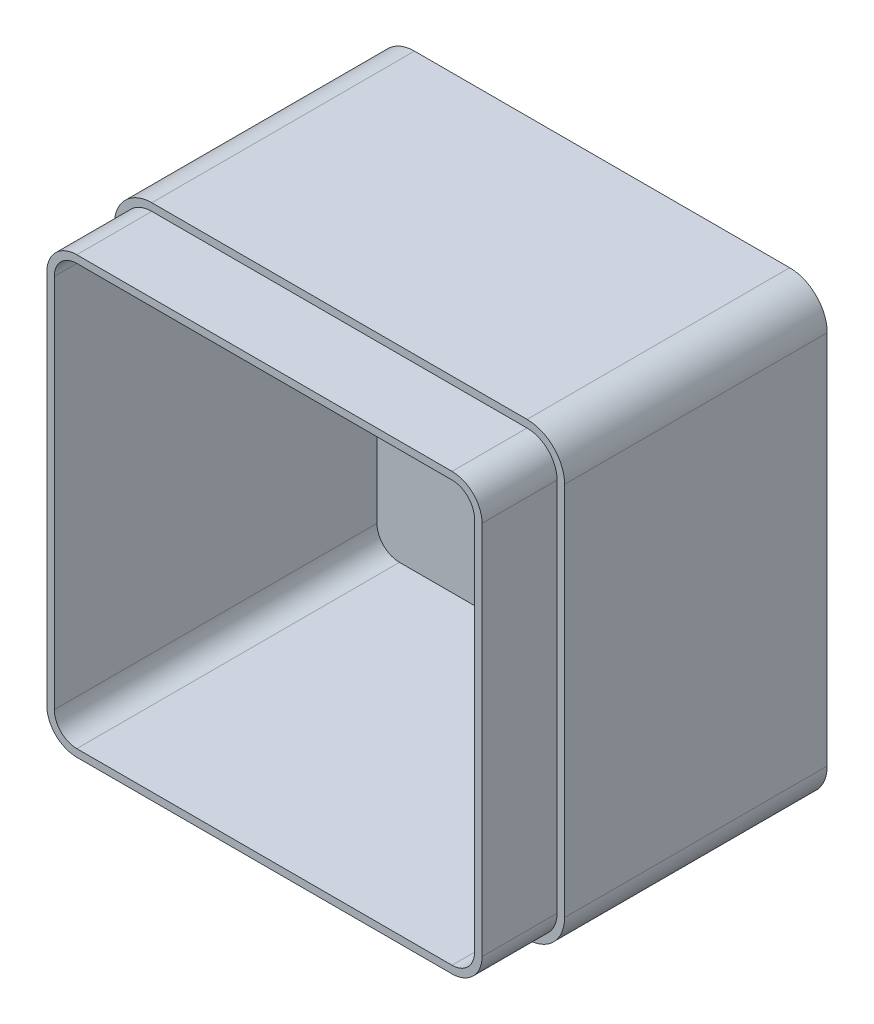
SolidWorks part; units mm, degrees
ref_plane "Front Plane" through (0, 0, 0) normal (0, 0, 1) x (1, 0, 0)
ref_plane "Top Plane" through (0, 0, 0) normal (0, 1, 0) x (1, 0, 0)
ref_plane "Right Plane" through (0, 0, 0) normal (1, 0, 0) x (0, 0, -1)
sketch "Sketch1" plane through (0, 0, 0) normal (0, 0, 1) x (1, 0, 0)
  line L1 (0, 0) -> (120, 0)
  line L2 (0, 0) -> (0, 120)
  line L3 (0, 120) -> (120, 120)
  line L4 (120, 0) -> (120, 120)
  dimension "D1" = 120
  dimension "D2" = 120
extrude "Boss-Extrude1" add sketch "Sketch1" along normal blind 90
fillet "Fillet1" radius 10 4 edges at (120, 0, 45) (0, 0, 45) (0, 120, 45) (120, 120, 45)
shell "Shell1" thickness 4
sketch "Sketch2" plane through (0, 0, 90) normal (0, 0, 1) x (1, 0, 0)
  line L4 (10, 0) -> (110, 0)
  line L5 (120, 10) -> (120, 110)
  line L6 (110, 120) -> (10, 120)
  line L7 (0, 110) -> (0, 10)
  line L8 (10, 0) -> (110, 0)
  line L9 (120, 10) -> (120, 110)
  line L10 (110, 120) -> (10, 120)
  line L11 (0, 110) -> (0, 10)
  arc A4 (110, 0) -> (120, 10) centre (110, 10) ccw
  arc A5 (120, 110) -> (110, 120) centre (110, 110) ccw
  arc A6 (10, 120) -> (0, 110) centre (10, 110) ccw
  arc A7 (0, 10) -> (10, 0) centre (10, 10) ccw
  arc A8 (110, 0) -> (120, 10) centre (110, 10) ccw
  arc A9 (120, 110) -> (110, 120) centre (110, 110) ccw
  arc A10 (10, 120) -> (0, 110) centre (10, 110) ccw
  arc A11 (0, 10) -> (10, 0) centre (10, 10) ccw
  dimension "D1" = 0
sketch "Sketch3" plane through (0, 0, 90) normal (0, 0, 1) x (1, 0, 0)
  line L4 (10, 0) -> (110, 0)
  line L5 (120, 10) -> (120, 110)
  line L6 (110, 120) -> (10, 120)
  line L7 (0, 110) -> (0, 10)
  line L8 (10, 0) -> (110, 0)
  line L9 (120, 10) -> (120, 110)
  line L10 (110, 120) -> (10, 120)
  line L11 (0, 110) -> (0, 10)
  line L16 (10, 2) -> (110, 2)
  line L17 (118, 10) -> (118, 110)
  line L18 (110, 118) -> (10, 118)
  line L19 (2, 110) -> (2, 10)
  line L20 (10, 2) -> (110, 2)
  line L21 (118, 10) -> (118, 110)
  line L22 (110, 118) -> (10, 118)
  line L23 (2, 110) -> (2, 10)
  arc A4 (110, 0) -> (120, 10) centre (110, 10) ccw
  arc A5 (120, 110) -> (110, 120) centre (110, 110) ccw
  arc A6 (10, 120) -> (0, 110) centre (10, 110) ccw
  arc A7 (0, 10) -> (10, 0) centre (10, 10) ccw
  arc A8 (110, 0) -> (120, 10) centre (110, 10) ccw
  arc A9 (120, 110) -> (110, 120) centre (110, 110) ccw
  arc A10 (10, 120) -> (0, 110) centre (10, 110) ccw
  arc A11 (0, 10) -> (10, 0) centre (10, 10) ccw
  arc A16 (110, 2) -> (118, 10) centre (110, 10) ccw
  arc A17 (118, 110) -> (110, 118) centre (110, 110) ccw
  arc A18 (10, 118) -> (2, 110) centre (10, 110) ccw
  arc A19 (2, 10) -> (10, 2) centre (10, 10) ccw
  arc A20 (110, 2) -> (118, 10) centre (110, 10) ccw
  arc A21 (118, 110) -> (110, 118) centre (110, 110) ccw
  arc A22 (10, 118) -> (2, 110) centre (10, 110) ccw
  arc A23 (2, 10) -> (10, 2) centre (10, 10) ccw
  dimension "D1" = 0
  dimension "D2" = 2
extrude "Cut-Extrude4" cut sketch "Sketch3" against normal blind 20
